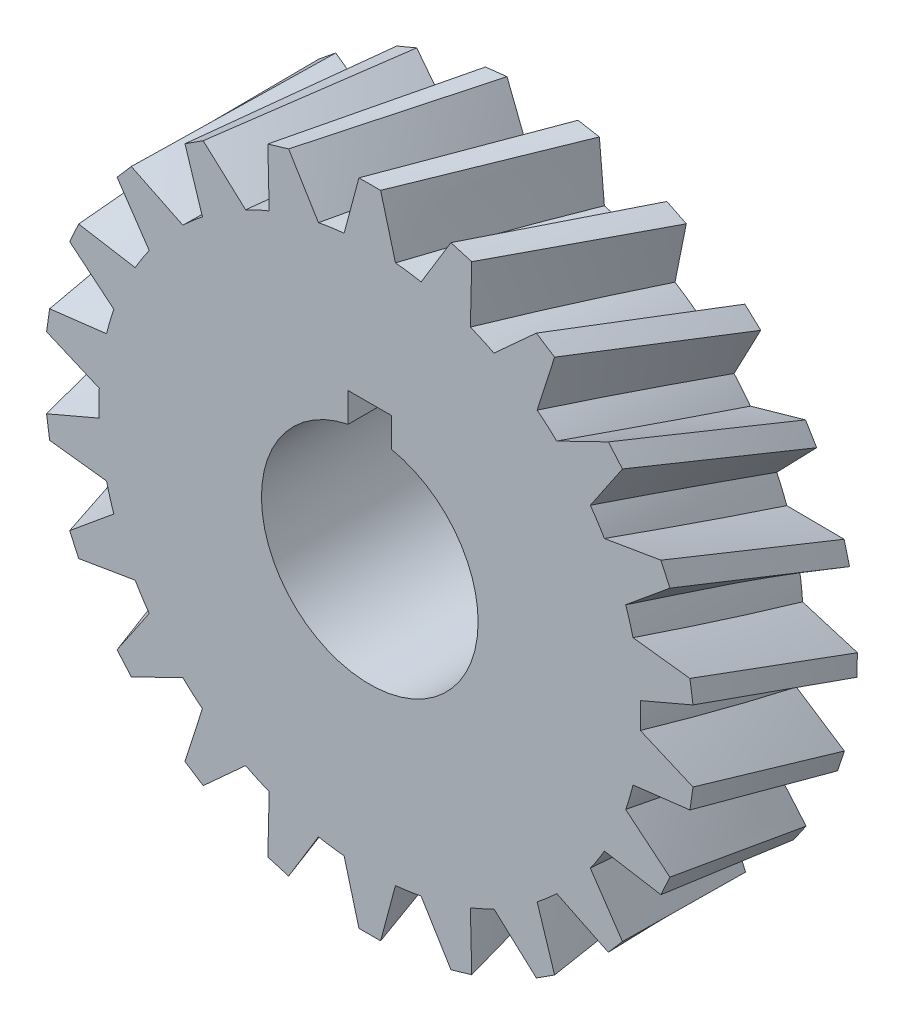
SolidWorks part; units mm, degrees
ref_plane "Front Plane" through (0, 0, 0) normal (0, 0, 1) x (1, 0, 0)
ref_plane "Top Plane" through (0, 0, 0) normal (0, 1, 0) x (1, 0, 0)
ref_plane "Right Plane" through (0, 0, 0) normal (1, 0, 0) x (0, 0, -1)
sketch "Sketch1" plane through (0, 0, 0) normal (0, 0, 1) x (1, 0, 0)
  circle A0 centre (0, 0) radius 12.7
  dimension "D1" = 25.4
extrude "Boss-Extrude1" add sketch "Sketch1" along normal blind 7.62
sketch "Sketch2" plane through (0, 0, 7.62) normal (0, 0, 1) x (1, 0, 0)
  line L0 (0, -1000) -> (0, 49000) construction
  line L1 (-1.3247, 12.192) -> (1.3247, 12.192)
  line L2 (1.3247, 12.192) -> (0.508, 15.24)
  line L3 (0.508, 15.24) -> (-0.508, 15.24)
  line L4 (-0.508, 15.24) -> (-1.3247, 12.192)
  dimension "D1" = 0.508
  dimension "D2" = 0.508
  dimension "D3" = 75
  dimension "D4" = 75
  dimension "D5" = 15.24
  dimension "D6" = 12.192
sketch "Sketch3" plane through (0, 0, 0) normal (0, 0, -1) x (-1, 0, 0)
  line L4 (-3.4217, 11.7767) -> (-3.1467, 14.9203)
  line L5 (-0.8125, 12.2368) -> (-3.4217, 11.7767)
  line L6 (-2.1461, 15.0967) -> (-0.8125, 12.2368)
  line L7 (-3.1467, 14.9203) -> (-2.1461, 15.0967)
  circle A2 centre (0, 0) radius 12.7
loft "Loft1" add profiles "Sketch2" section "Sketch2" section "Sketch3"
pattern_circular "CirPattern1" count 22 over 360 about axis through (0, 0, 7.62) along (0, 0, -1) of "Loft1"
sketch "Sketch4" plane through (0, 0, 0) normal (0, 0, -1) x (-1, 0, 0)
  circle A0 centre (0, 0) radius 5.08
  dimension "D1" = 10.16
extrude "Cut-Extrude1" cut sketch "Sketch4" against normal through all
sketch "Sketch5" plane through (0, 0, 0) normal (0, 0, -1) x (-1, 0, 0)
  line L1 (-1.016, 6.35) -> (1.016, 6.35)
  line L2 (-1.016, 6.35) -> (-1.016, 3.81)
  line L3 (-1.016, 3.81) -> (1.016, 3.81)
  line L4 (1.016, 6.35) -> (1.016, 3.81)
  point P4 (0, 3.81)
  dimension "D1" = 3.81
  dimension "D2" = 2.54
  dimension "D3" = 2.032
extrude "Cut-Extrude2" cut sketch "Sketch5" against normal through all
